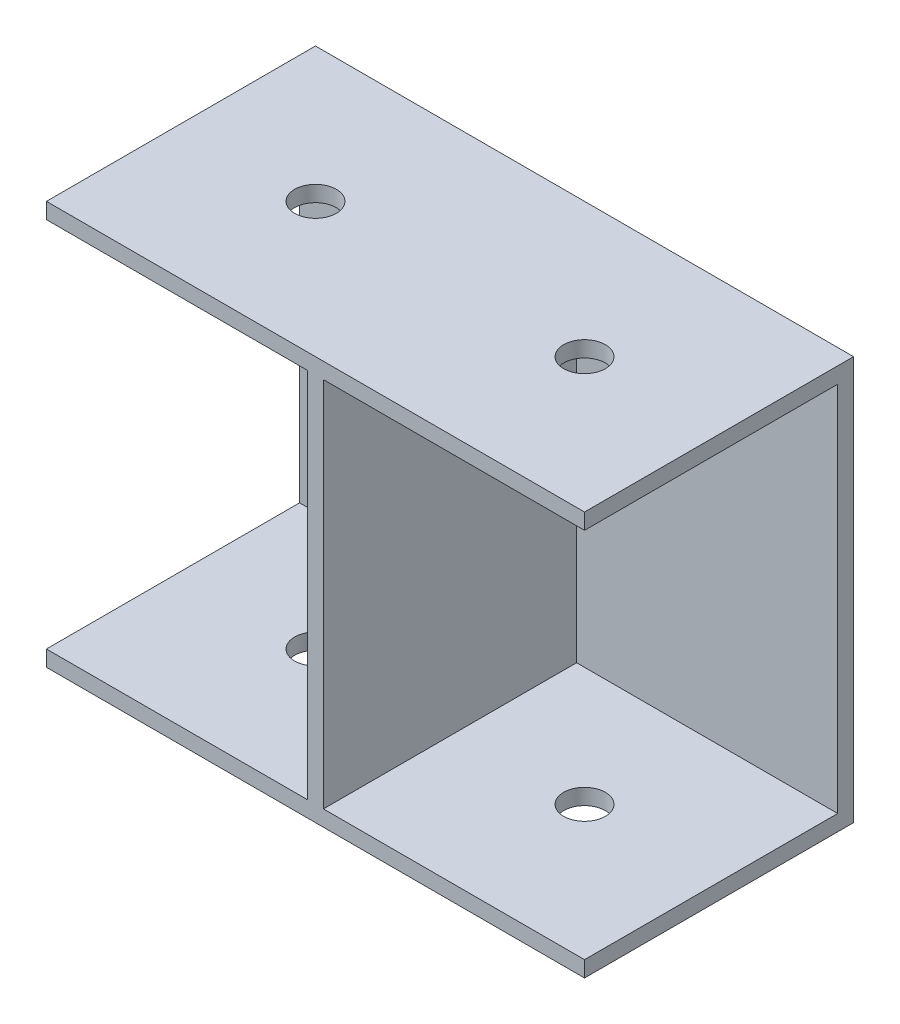
SolidWorks part; units mm, degrees
ref_plane "Front Plane" through (0, 0, 0) normal (0, 0, 1) x (1, 0, 0)
ref_plane "Top Plane" through (0, 0, 0) normal (0, 1, 0) x (1, 0, 0)
ref_plane "Right Plane" through (0, 0, 0) normal (1, 0, 0) x (0, 0, -1)
sketch "Sketch1" plane through (0, 0, 0) normal (0, 0, 1) x (1, 0, 0)
  line L1 (-50.8, -38.1) -> (50.8, -38.1)
  line L2 (-50.8, -38.1) -> (-50.8, 38.1)
  line L3 (-50.8, 38.1) -> (50.8, 38.1)
  line L4 (50.8, -38.1) -> (50.8, 38.1)
  line L5 (-50.8, -38.1) -> (50.8, 38.1) construction
  line L6 (-50.8, 38.1) -> (50.8, -38.1) construction
  point P0 (50.8, 38.1)
  point P1 (0, 0)
extrude "Boss-Extrude1" add sketch "Sketch1" along normal blind 50.8
sketch3d "3DSketch2" plane through (0, 0, 0) normal (0, 0, 1) x (1, 0, 0)
sketch "Sketch3" plane through (0, 0, 50.8) normal (0, 0, 1) x (1, 0, 0)
  line L0 (0, 0) -> (0, 61.044) construction
  line L1 (-50.8, -35.1) -> (-50.8, 35.1)
  line L2 (1.5, -35.1) -> (50.8, -35.1)
  line L3 (1.5, -35.1) -> (1.5, 35.1)
  line L4 (1.5, 35.1) -> (50.8, 35.1)
  line L5 (50.8, -35.1) -> (50.8, 35.1)
  line L6 (-1.5, 35.1) -> (-50.8, 35.1)
  line L7 (-1.5, -35.1) -> (-1.5, 35.1)
  line L8 (-1.5, -35.1) -> (-50.8, -35.1)
  point P0 (50.8, 22.4)
  point P1 (1.5, -47.8)
extrude "Cut-Extrude1" cut sketch "Sketch3" against normal blind 47.8
sketch "Sketch4" plane through (0, 0, 0) normal (0, 1, 0) x (1, 0, 0)
  line L0 (0, 0) -> (0, -23.5943) construction
  circle A0 centre (25.4, -25.4) radius 3.937
  circle A1 centre (-25.4, -25.4) radius 3.937
  point P0 (25.4, -25.4)
extrude "Cut-Extrude3" cut sketch "Sketch4" against normal mid plane 101.6
